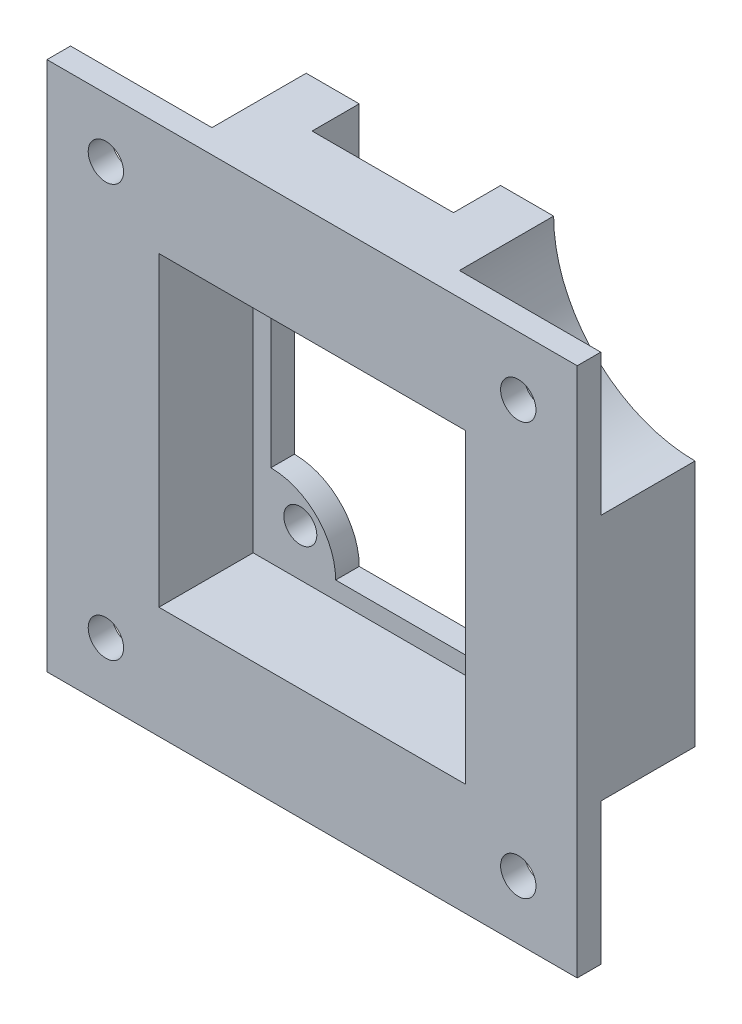
SolidWorks part; units mm, degrees
ref_plane "Alzado" through (0, 0, 0) normal (0, 0, 1) x (1, 0, 0)
ref_plane "Planta" through (0, 0, 0) normal (0, 1, 0) x (1, 0, 0)
ref_plane "Vista lateral" through (0, 0, 0) normal (1, 0, 0) x (0, 0, -1)
sketch "Croquis1" plane through (0, 0, 0) normal (0, 0, 1) x (1, 0, 0)
  line L1 (-22.5, -22.5) -> (22.5, -22.5)
  line L2 (-22.5, -22.5) -> (-22.5, 22.5)
  line L3 (-22.5, 22.5) -> (22.5, 22.5)
  line L4 (22.5, -22.5) -> (22.5, 22.5)
  line L5 (-22.5, -22.5) -> (22.5, 22.5) construction
  line L6 (-22.5, 22.5) -> (22.5, -22.5) construction
  point P0 (0, 0)
extrude "Saliente-Extruir1" add sketch "Croquis1" along normal blind 10
sketch "Croquis2" plane through (0, 0, 10) normal (0, 0, 1) x (1, 0, 0)
  line L1 (-11.5, -11.5) -> (11.5, -11.5)
  line L2 (-11.5, -11.5) -> (-11.5, 11.5)
  line L3 (-11.5, 11.5) -> (11.5, 11.5)
  line L4 (11.5, -11.5) -> (11.5, 11.5)
  line L5 (-11.5, -11.5) -> (11.5, 11.5) construction
  line L6 (-11.5, 11.5) -> (11.5, -11.5) construction
  arc A0 (-6, 11.5) -> (-11.5, 6) centre (-11.5, 11.5) cw
  arc A1 (11.5, 6) -> (6, 11.5) centre (11.5, 11.5) cw
  arc A2 (-6, -11.5) -> (-11.5, -6) centre (-11.5, -11.5) ccw
  arc A3 (6, -11.5) -> (11.5, -6) centre (11.5, -11.5) cw
  point P0 (0, 0)
extrude "Cortar-Extruir1" cut sketch "Croquis2" against normal blind 10 contours L1 A3 L4 A1 L3 A0 L2 A2
sketch "Croquis3" plane through (0, 0, 10) normal (0, 0, 1) x (1, 0, 0)
  line L1 (-13, -13) -> (13, -13)
  line L2 (-13, -13) -> (-13, 13)
  line L3 (-13, 13) -> (13, 13)
  line L4 (13, -13) -> (13, 13)
  line L5 (-13, -13) -> (13, 13) construction
  line L6 (-13, 13) -> (13, -13) construction
  point P0 (0, 0)
extrude "Cortar-Extruir5" cut sketch "Croquis3" against normal blind 8
sketch "Croquis4" plane through (0, 0, 0) normal (0, 0, -1) x (-1, 0, 0)
  line L0 (-6, 11.5) -> (6, 11.5)
  line L1 (6, 11.5) -> (6, 22.5)
  line L2 (-22.5, 22.5) -> (22.5, 22.5) construction
  line L3 (6, 22.5) -> (-6, 22.5)
  line L4 (-6, 22.5) -> (-6, 11.5)
extrude "Cortar-Extruir6" cut sketch "Croquis4" against normal blind 4
sketch "Croquis5" plane through (0, 0, 0) normal (0, 0, -1) x (-1, 0, 0)
  line L0 (-11.5, 0) -> (-9, 0) construction
  line L1 (11.5, 0) -> (9, 0) construction
  line L2 (-11.5, -11.5) -> (11.5, -11.5)
  line L3 (-11.5, -11.5) -> (-11.5, 11.5)
  line L4 (-11.5, 11.5) -> (11.5, 11.5)
  line L5 (11.5, -11.5) -> (11.5, 11.5)
  line L6 (-11.5, -11.5) -> (11.5, 11.5) construction
  line L7 (-11.5, 11.5) -> (11.5, -11.5) construction
  line L8 (0, 11.5) -> (0, 9) construction
  line L9 (0, -11.5) -> (0, -9) construction
  line L15 (-8.5, -8.5) -> (8.5, 8.5) construction
  line L16 (-8.5, 8.5) -> (8.5, -8.5) construction
  line L17 (-9, -9) -> (9, -9)
  line L18 (-9, -9) -> (-9, 9)
  line L19 (-9, 9) -> (9, 9)
  line L20 (9, -9) -> (9, 9)
  line L21 (-9, -9) -> (9, 9) construction
  line L22 (-9, 9) -> (9, -9) construction
  circle A0 centre (-9, 9) radius 1.4
  circle A1 centre (9, 9) radius 1.4
  circle A2 centre (-9, -9) radius 1.4
  circle A3 centre (9, -9) radius 1.4
  point P0 (0, 0)
  point P14 (0, 0)
  point P19 (0, 0)
extrude "Cortar-Extruir7" cut sketch "Croquis5" against normal blind 4 contours L19 A0 L18 | L18 A0 L19 | L20 A1 L19 | L19 A1 L20 | L17 A3 L20 | L20 A3 L17 | L18 A2 L17 | L17 A2 L18
sketch "Croquis6" plane through (0, 0, 0) normal (0, 0, -1) x (-1, 0, 0)
  line L0 (-22.5, 22.5) -> (-17.5, 22.5) construction
  line L1 (-22.5, 22.5) -> (-6, 22.5) construction
  line L2 (-17.5, 22.5) -> (-17.5, 17.5) construction
  line L3 (-17.5, -22.5) -> (-17.5, -17.5) construction
  line L4 (22.5, -22.5) -> (-22.5, -22.5) construction
  line L5 (22.5, -17.5) -> (17.5, -17.5) construction
  line L6 (22.5, 22.5) -> (22.5, -22.5) construction
  line L7 (17.5, 22.5) -> (17.5, 17.5) construction
  line L8 (6, 22.5) -> (22.5, 22.5) construction
  circle A0 centre (-17.5, 17.5) radius 1.5
  circle A1 centre (-17.5, -17.5) radius 1.5
  circle A2 centre (17.5, -17.5) radius 1.5
  circle A3 centre (17.5, 17.5) radius 1.5
extrude "Cortar-Extruir8" cut sketch "Croquis6" against normal blind 24
sketch "Croquis7" plane through (0, 0, 0) normal (0, 0, -1) x (-1, 0, 0)
  line L0 (-22.5, 22.5) -> (-6, 22.5) construction
  line L1 (-22.5, -22.5) -> (-22.5, 22.5) construction
  line L2 (22.5, -22.5) -> (-22.5, -22.5) construction
  line L3 (22.5, 22.5) -> (22.5, -22.5) construction
  line L4 (6, 22.5) -> (22.5, 22.5) construction
  line L6 (22.5, -22.5) -> (-22.5, -22.5)
  line L7 (22.5, -22.5) -> (22.5, 22.5)
  line L8 (22.5, 22.5) -> (-22.5, 22.5)
  line L9 (-22.5, -22.5) -> (-22.5, 22.5)
  line L10 (22.5, -22.5) -> (-22.5, 22.5) construction
  line L11 (22.5, 22.5) -> (-22.5, -22.5) construction
  arc A0 (-10.5, 22.5) -> (-22.5, 10.5) centre (-22.5, 22.5) cw
  arc A1 (-10.5, -22.5) -> (-22.5, -10.5) centre (-22.5, -22.5) ccw
  arc A2 (22.5, -10.5) -> (10.5, -22.5) centre (22.5, -22.5) ccw
  arc A3 (22.5, 10.5) -> (10.5, 22.5) centre (22.5, 22.5) cw
  point P26 (0, 0)
  circle M5 centre (17.5, 17.5) radius 1.5
  circle M6 centre (17.5, -17.5) radius 1.5
  circle M7 centre (-17.5, -17.5) radius 1.5
  circle M8 centre (-17.5, 17.5) radius 1.5
  line M15 (-22.5, 22.5) -> (-22.5, -22.5)
  line M16 (-22.5, -22.5) -> (22.5, -22.5)
  line M17 (22.5, -22.5) -> (22.5, 22.5)
  line M18 (22.5, 22.5) -> (6, 22.5)
extrude "Cortar-Extruir9" cut sketch "Croquis7" against normal blind 8 contours A0 L8 M15 M8 | A3 M17 M18 M5 | A2 M17 M16 M6 | A1 M16 M15 M7
